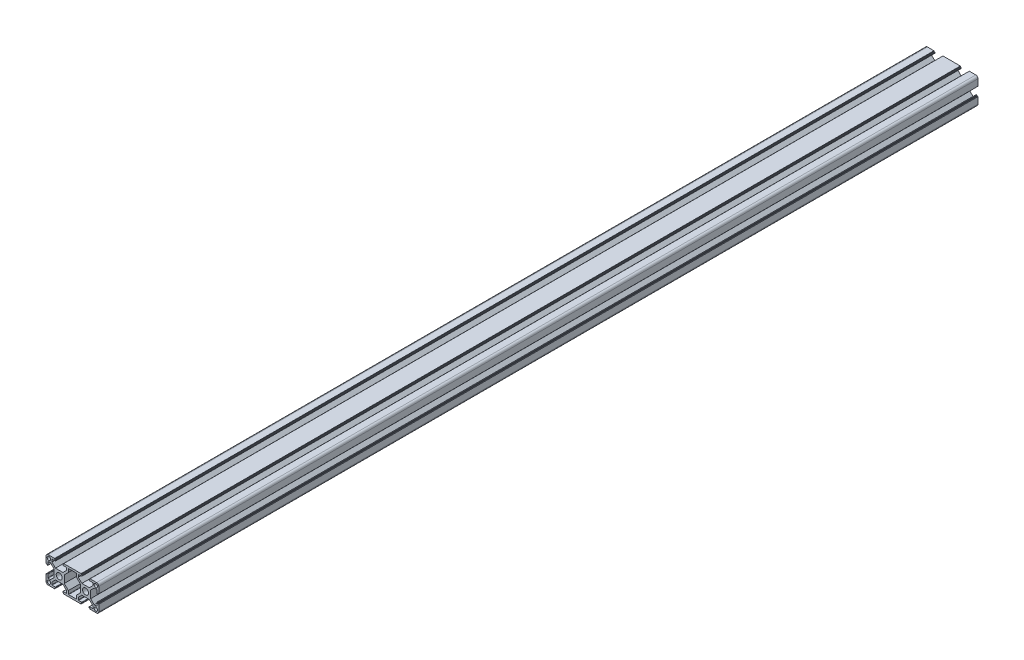
SolidWorks part; units mm, degrees
ref_plane "前视基准面" through (0, 0, 0) normal (0, 0, 1) x (1, 0, 0)
ref_plane "上视基准面" through (0, 0, 0) normal (0, 1, 0) x (1, 0, 0)
ref_plane "右视基准面" through (0, 0, 0) normal (1, 0, 0) x (0, 0, -1)
sketch "草图1" plane through (0, 0, 0) normal (0, 0, 1) x (1, 0, 0)
  line L1 (-17.624, -4.6898) -> (-17.624, 3.7989)
  line L3 (-10.924, 14.5545) -> (-18.324, 14.5545)
  line L4 (-18.324, 14.5545) -> (-18.324, 13.7545)
  line L5 (-18.524, 13.5545) -> (-19.324, 13.5545)
  line L6 (-19.324, 13.5545) -> (-19.324, 12.6545)
  line L7 (-19.024, 12.3545) -> (-15.474, 12.3545)
  line L8 (-15.174, 12.0545) -> (-15.174, 9.3602)
  line L9 (-15.174, 9.3602) -> (-19.1797, 5.3545)
  line L10 (-19.1797, 5.3545) -> (-27.6684, 5.3545)
  line L11 (-27.6684, 5.3545) -> (-31.674, 9.3602)
  line L12 (-31.674, 9.3602) -> (-31.674, 12.0545)
  line L13 (-31.374, 12.3545) -> (-27.824, 12.3545)
  line L14 (-27.524, 12.6545) -> (-27.524, 13.5545)
  line L15 (-27.524, 13.5545) -> (-28.324, 13.5545)
  line L16 (-28.524, 13.7545) -> (-28.524, 14.5545)
  line L17 (-28.524, 14.5545) -> (-35.924, 14.5545)
  line L18 (-38.424, 12.0545) -> (-38.424, 4.6545)
  line L19 (-38.424, 4.6545) -> (-37.624, 4.6545)
  line L20 (-37.424, 4.4545) -> (-37.424, 3.6545)
  line L21 (-37.424, 3.6545) -> (-36.524, 3.6545)
  line L22 (-36.224, 3.9545) -> (-36.224, 7.5045)
  line L23 (-35.924, 7.8045) -> (-33.2297, 7.8045)
  line L24 (-33.2297, 7.8045) -> (-29.224, 3.7989)
  line L25 (-29.224, 3.7989) -> (-29.224, -4.6898)
  line L26 (-29.224, -4.6898) -> (-33.2297, -8.6955)
  line L27 (-33.2297, -8.6955) -> (-35.924, -8.6955)
  line L28 (-36.224, -8.3955) -> (-36.224, -4.8455)
  line L29 (-36.524, -4.5455) -> (-37.424, -4.5455)
  line L30 (-37.424, -4.5455) -> (-37.424, -5.3455)
  line L31 (-37.624, -5.5455) -> (-38.424, -5.5455)
  line L32 (-38.424, -5.5455) -> (-38.424, -12.9455)
  line L33 (-35.924, -15.4455) -> (-28.524, -15.4455)
  line L34 (-28.524, -15.4455) -> (-28.524, -14.6455)
  line L35 (-28.324, -14.4455) -> (-27.524, -14.4455)
  line L36 (-27.524, -14.4455) -> (-27.524, -13.5455)
  line L37 (-27.824, -13.2455) -> (-31.374, -13.2455)
  line L38 (-31.674, -12.9455) -> (-31.674, -10.2511)
  line L39 (-31.674, -10.2511) -> (-27.6684, -6.2455)
  line L40 (-27.6684, -6.2455) -> (-19.1797, -6.2455)
  line L41 (-19.1797, -6.2455) -> (-15.174, -10.2511)
  line L42 (-15.174, -10.2511) -> (-15.174, -12.9455)
  line L43 (-15.474, -13.2455) -> (-19.024, -13.2455)
  line L44 (-19.324, -13.5455) -> (-19.324, -14.4455)
  line L45 (-19.324, -14.4455) -> (-18.524, -14.4455)
  line L46 (-18.324, -14.6455) -> (-18.324, -15.4455)
  line L47 (-18.324, -15.4455) -> (-10.924, -15.4455)
  line L48 (-5.924, -15.4455) -> (1.476, -15.4455)
  line L49 (1.476, -15.4455) -> (1.476, -14.6455)
  line L50 (1.676, -14.4455) -> (2.476, -14.4455)
  line L51 (2.476, -14.4455) -> (2.476, -13.5455)
  line L52 (2.176, -13.2455) -> (-1.374, -13.2455)
  line L53 (-1.674, -12.9455) -> (-1.674, -10.2511)
  line L54 (-1.674, -10.2511) -> (2.3316, -6.2455)
  line L55 (2.3316, -6.2455) -> (10.8203, -6.2455)
  line L56 (10.8203, -6.2455) -> (14.826, -10.2511)
  line L57 (14.826, -10.2511) -> (14.826, -12.9455)
  line L58 (14.526, -13.2455) -> (10.976, -13.2455)
  line L59 (10.676, -13.5455) -> (10.676, -14.4455)
  line L60 (10.676, -14.4455) -> (11.476, -14.4455)
  line L61 (11.676, -14.6455) -> (11.676, -15.4455)
  line L62 (11.676, -15.4455) -> (19.076, -15.4455)
  line L63 (21.576, -12.9455) -> (21.576, -5.5455)
  line L64 (21.576, -5.5455) -> (20.776, -5.5455)
  line L65 (20.576, -5.3455) -> (20.576, -4.5455)
  line L66 (20.576, -4.5455) -> (19.676, -4.5455)
  line L67 (19.376, -4.8455) -> (19.376, -8.3955)
  line L68 (19.076, -8.6955) -> (16.3816, -8.6955)
  line L69 (16.3816, -8.6955) -> (12.376, -4.6898)
  line L70 (12.376, -4.6898) -> (12.376, 3.7989)
  line L71 (12.376, 3.7989) -> (16.3816, 7.8045)
  line L72 (16.3816, 7.8045) -> (19.076, 7.8045)
  line L73 (19.376, 7.5045) -> (19.376, 3.9545)
  line L74 (19.676, 3.6545) -> (20.576, 3.6545)
  line L75 (20.576, 3.6545) -> (20.576, 4.4545)
  line L76 (20.776, 4.6545) -> (21.576, 4.6545)
  line L77 (21.576, 4.6545) -> (21.576, 12.0545)
  line L78 (19.076, 14.5545) -> (11.676, 14.5545)
  line L79 (11.676, 14.5545) -> (11.676, 13.7545)
  line L80 (11.476, 13.5545) -> (10.676, 13.5545)
  line L81 (10.676, 13.5545) -> (10.676, 12.6545)
  line L82 (10.976, 12.3545) -> (14.526, 12.3545)
  line L83 (14.826, 12.0545) -> (14.826, 9.3602)
  line L84 (14.826, 9.3602) -> (10.8203, 5.3545)
  line L85 (10.8203, 5.3545) -> (2.3316, 5.3545)
  line L86 (2.3316, 5.3545) -> (-1.674, 9.3602)
  line L87 (-1.674, 9.3602) -> (-1.674, 12.0545)
  line L88 (-1.374, 12.3545) -> (2.176, 12.3545)
  line L89 (2.476, 12.6545) -> (2.476, 13.5545)
  line L90 (2.476, 13.5545) -> (1.676, 13.5545)
  line L91 (1.476, 13.7545) -> (1.476, 14.5545)
  line L92 (1.476, 14.5545) -> (-5.924, 14.5545)
  line L94 (0.776, 3.7989) -> (0.776, -4.6898)
  line L96 (-10.924, -15.4455) -> (-5.924, -15.4455)
  line L97 (-10.924, 14.5545) -> (-5.924, 14.5545)
  line L99 (-12.974, 8.4489) -> (-12.974, 12.0545)
  line L100 (-12.674, 12.3545) -> (-4.174, 12.3545)
  line L101 (-3.874, 12.0545) -> (-3.874, 8.4489)
  line L102 (-3.874, 8.4489) -> (0.776, 3.7989)
  line L105 (-3.874, -9.3398) -> (-3.874, -12.9455)
  line L106 (-4.174, -13.2455) -> (-12.674, -13.2455)
  line L107 (-12.974, -12.9455) -> (-12.974, -9.3398)
  line L108 (-12.974, -9.3398) -> (-17.624, -4.6898)
  line L110 (-17.624, 3.7989) -> (-12.974, 8.4489)
  line L116 (0.776, -4.6898) -> (-3.874, -9.3398)
  arc A1 (-18.524, 13.5545) -> (-18.324, 13.7545) centre (-18.524, 13.7545) ccw
  arc A2 (-19.324, 12.6545) -> (-19.024, 12.3545) centre (-19.024, 12.6545) ccw
  arc A3 (-15.174, 12.0545) -> (-15.474, 12.3545) centre (-15.474, 12.0545) ccw
  arc A4 (-31.374, 12.3545) -> (-31.674, 12.0545) centre (-31.374, 12.0545) ccw
  arc A5 (-27.824, 12.3545) -> (-27.524, 12.6545) centre (-27.824, 12.6545) ccw
  arc A6 (-28.524, 13.7545) -> (-28.324, 13.5545) centre (-28.324, 13.7545) ccw
  arc A7 (-35.924, 14.5545) -> (-38.424, 12.0545) centre (-35.924, 12.0545) ccw
  arc A8 (-37.424, 4.4545) -> (-37.624, 4.6545) centre (-37.624, 4.4545) ccw
  arc A9 (-36.524, 3.6545) -> (-36.224, 3.9545) centre (-36.524, 3.9545) ccw
  arc A10 (-35.924, 7.8045) -> (-36.224, 7.5045) centre (-35.924, 7.5045) ccw
  arc A11 (-36.224, -8.3955) -> (-35.924, -8.6955) centre (-35.924, -8.3955) ccw
  arc A12 (-36.224, -4.8455) -> (-36.524, -4.5455) centre (-36.524, -4.8455) ccw
  arc A13 (-37.624, -5.5455) -> (-37.424, -5.3455) centre (-37.624, -5.3455) ccw
  arc A14 (-38.424, -12.9455) -> (-35.924, -15.4455) centre (-35.924, -12.9455) ccw
  arc A15 (-28.324, -14.4455) -> (-28.524, -14.6455) centre (-28.324, -14.6455) ccw
  arc A16 (-27.524, -13.5455) -> (-27.824, -13.2455) centre (-27.824, -13.5455) ccw
  arc A17 (-31.674, -12.9455) -> (-31.374, -13.2455) centre (-31.374, -12.9455) ccw
  arc A18 (-15.474, -13.2455) -> (-15.174, -12.9455) centre (-15.474, -12.9455) ccw
  arc A19 (-19.024, -13.2455) -> (-19.324, -13.5455) centre (-19.024, -13.5455) ccw
  arc A20 (-18.324, -14.6455) -> (-18.524, -14.4455) centre (-18.524, -14.6455) ccw
  arc A24 (1.676, -14.4455) -> (1.476, -14.6455) centre (1.676, -14.6455) ccw
  arc A25 (2.476, -13.5455) -> (2.176, -13.2455) centre (2.176, -13.5455) ccw
  arc A26 (-1.674, -12.9455) -> (-1.374, -13.2455) centre (-1.374, -12.9455) ccw
  arc A27 (14.526, -13.2455) -> (14.826, -12.9455) centre (14.526, -12.9455) ccw
  arc A28 (10.976, -13.2455) -> (10.676, -13.5455) centre (10.976, -13.5455) ccw
  arc A29 (11.676, -14.6455) -> (11.476, -14.4455) centre (11.476, -14.6455) ccw
  arc A30 (19.076, -15.4455) -> (21.576, -12.9455) centre (19.076, -12.9455) ccw
  arc A31 (20.576, -5.3455) -> (20.776, -5.5455) centre (20.776, -5.3455) ccw
  arc A32 (19.676, -4.5455) -> (19.376, -4.8455) centre (19.676, -4.8455) ccw
  arc A33 (19.076, -8.6955) -> (19.376, -8.3955) centre (19.076, -8.3955) ccw
  arc A34 (19.376, 7.5045) -> (19.076, 7.8045) centre (19.076, 7.5045) ccw
  arc A35 (19.376, 3.9545) -> (19.676, 3.6545) centre (19.676, 3.9545) ccw
  arc A36 (20.776, 4.6545) -> (20.576, 4.4545) centre (20.776, 4.4545) ccw
  arc A37 (21.576, 12.0545) -> (19.076, 14.5545) centre (19.076, 12.0545) ccw
  arc A38 (11.476, 13.5545) -> (11.676, 13.7545) centre (11.476, 13.7545) ccw
  arc A39 (10.676, 12.6545) -> (10.976, 12.3545) centre (10.976, 12.6545) ccw
  arc A40 (14.826, 12.0545) -> (14.526, 12.3545) centre (14.526, 12.0545) ccw
  arc A41 (-1.374, 12.3545) -> (-1.674, 12.0545) centre (-1.374, 12.0545) ccw
  arc A42 (2.176, 12.3545) -> (2.476, 12.6545) centre (2.176, 12.6545) ccw
  arc A43 (1.476, 13.7545) -> (1.676, 13.5545) centre (1.676, 13.7545) ccw
  arc A46 (-12.674, 12.3545) -> (-12.974, 12.0545) centre (-12.674, 12.0545) ccw
  arc A47 (-3.874, 12.0545) -> (-4.174, 12.3545) centre (-4.174, 12.0545) ccw
  arc A48 (-4.174, -13.2455) -> (-3.874, -12.9455) centre (-4.174, -12.9455) ccw
  arc A49 (-12.974, -12.9455) -> (-12.674, -13.2455) centre (-12.674, -12.9455) ccw
  circle A50 centre (18.201, -12.0705) radius 2
  circle A51 centre (18.201, 11.1795) radius 2
  circle A52 centre (6.576, -0.4455) radius 3.4
  circle A53 centre (-35.049, -12.0705) radius 2
  circle A54 centre (-35.049, 11.1795) radius 2
  circle A59 centre (-23.424, -0.4455) radius 3.4
extrude "凸台-拉伸1" add sketch "草图1" along normal blind 1000
